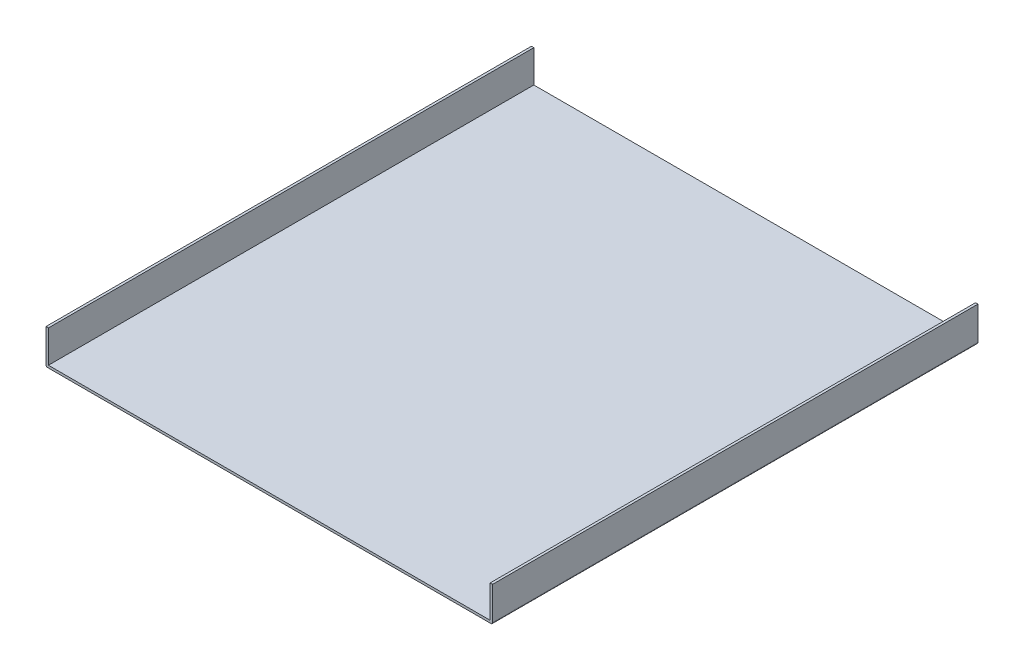
SolidWorks part; units mm, degrees
ref_plane "Front Plane" through (0, 0, 0) normal (0, 0, 1) x (1, 0, 0)
ref_plane "Top Plane" through (0, 0, 0) normal (0, 1, 0) x (1, 0, 0)
ref_plane "Right Plane" through (0, 0, 0) normal (1, 0, 0) x (0, 0, -1)
sketch "Sketch1" plane through (0, 0, 0) normal (0, 1, 0) x (1, 0, 0)
  line L1 (-138, -150) -> (138, -150)
  line L2 (-138, -150) -> (-138, 150)
  line L3 (-138, 150) -> (138, 150)
  line L4 (138, -150) -> (138, 150)
  line L5 (-138, -150) -> (138, 150) construction
  line L6 (-138, 150) -> (138, -150) construction
  point P0 (0, 0)
  dimension "D1" = 276
  dimension "D2" = 300
extrude "Boss-Extrude1" add sketch "Sketch1" along normal blind 1.5 contours L2 L3 L4 L1
sketch "Sketch2" plane through (0, 1.5, 0) normal (0, 1, 0) x (1, 0, 0)
  line L0 (-138, 150) -> (138, 150) construction
  line L1 (-138, -150) -> (-136.5, -150)
  line L2 (-138, -150) -> (-138, 150)
  line L3 (-138, 150) -> (-136.5, 150)
  line L4 (-136.5, -150) -> (-136.5, 150)
  line L6 (138, -150) -> (136.5, -150)
  line L7 (138, -150) -> (138, 150)
  line L8 (138, 150) -> (136.5, 150)
  line L9 (136.5, -150) -> (136.5, 150)
  dimension "D1" = 1.5
  dimension "D2" = 1.5
extrude "Boss-Extrude2" add sketch "Sketch2" along normal blind 20
sketch "Sketch3" plane through (-138, 0, 0) normal (-1, 0, 0) x (0, 0, 1)
  line L0 (-150, 21.5) -> (-150, 0) construction
  line L1 (150, 0) -> (-150, 0)
  line L2 (150, 0) -> (150, 1.5)
  line L3 (150, 1.5) -> (-150, 1.5)
  line L4 (-150, 0) -> (-150, 1.5)
  dimension "D1" = 1.5
extrude "Boss-Extrude3" [suppressed] add sketch "Sketch3" along normal blind 20
sketch "Sketch4" plane through (138, 0, 0) normal (1, 0, 0) x (0, 0, -1)
  line L0 (-150, 21.5) -> (-150, 0) construction
  line L1 (150, 0) -> (-150, 0)
  line L2 (150, 0) -> (150, 1.5)
  line L3 (150, 1.5) -> (-150, 1.5)
  line L4 (-150, 0) -> (-150, 1.5)
  dimension "D1" = 1.5
extrude "Boss-Extrude4" [suppressed] add sketch "Sketch4" along normal blind 20
fillet "Fillet1" radius 1 2 edges at (-138, 0, 0) (138, 0, 0)
